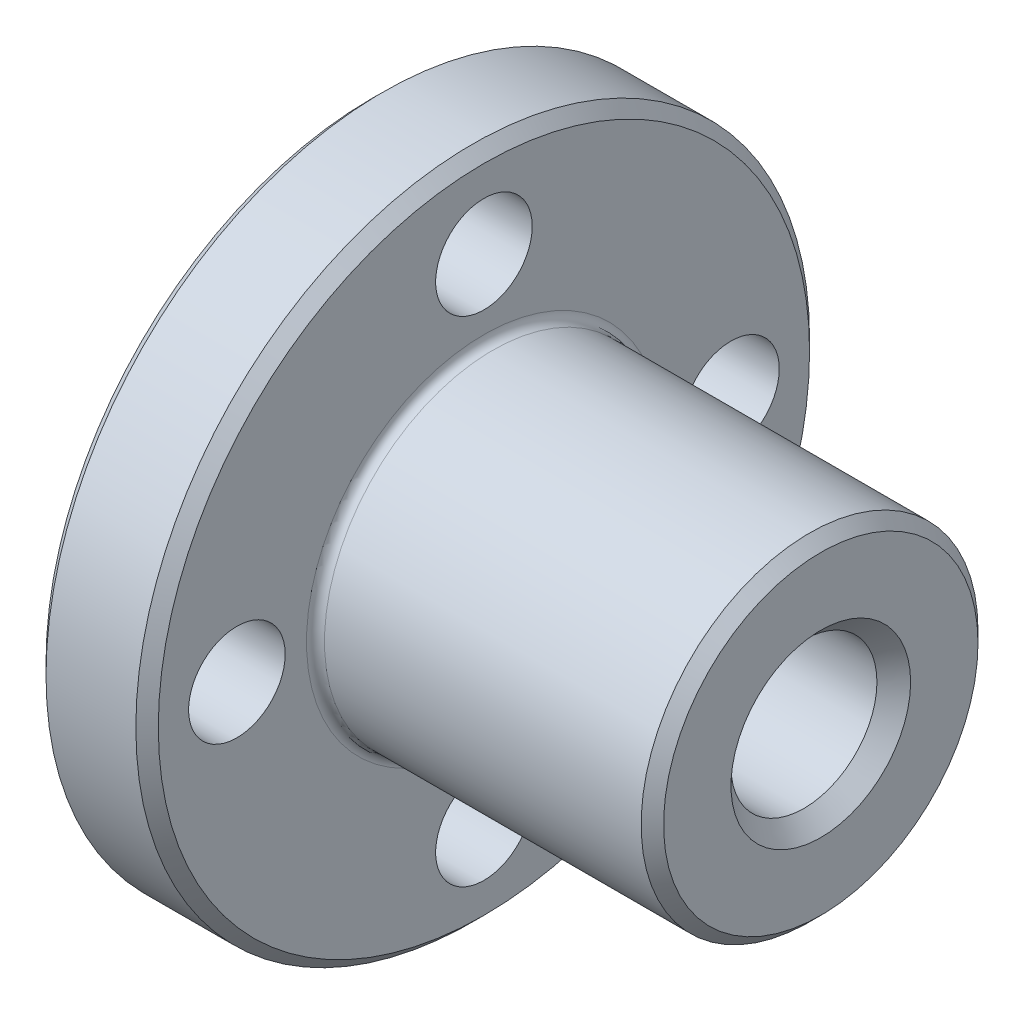
SolidWorks part; units mm, degrees
ref_plane "Front Plane" through (0, 0, 0) normal (0, 0, 1) x (1, 0, 0)
ref_plane "Top Plane" through (0, 0, 0) normal (0, 1, 0) x (1, 0, 0)
ref_plane "Right Plane" through (0, 0, 0) normal (1, 0, 0) x (0, 0, -1)
ref_plane "Plane1" through (0, 0, 0) normal (0, 0, -1) x (-1, 0, 0)
sketch "Sketch1" plane through (0, 0, 0) normal (0, 0, -1) x (-1, 0, 0)
  line L0 (-5, 15) -> (-5, 0)
  line L1 (-5, 0) -> (0, 0)
  line L2 (0, 0) -> (0, 15)
  line L3 (0, 15) -> (-5, 15)
  line L4 (-5, 0) -> (0, 0) construction
revolve "Revolve1" add sketch "Sketch1" angle 360 about L4
sketch "Sketch2" plane through (5, 0, 0) normal (1, 0, 0) x (0, 0, -1)
  circle A0 centre (0, 0) radius 7.5
extrude "Boss-Extrude1" add sketch "Sketch2" along normal blind 15
hole_wizard "Ø4.3 (4.3) Diameter Hole1" positions "Sketch4" profile "Sketch3" hole size "Ø4.3" standard "ANSI Metric"
sketch "Sketch4" plane through (5, 0, 0) normal (1, 0, 0) x (0, 0, -1)
  point P0 (-11, 0)
  point P1 (11, 0)
  point P2 (0, -11)
  point P3 (0, 11)
sketch "Sketch3" plane through (5, 0, 11) normal (0, 1, 0) x (0, 0, -1)
  line L0 (0, 0) -> (0, 5)
  line L1 (0, 5) -> (2.15, 5)
  line L2 (2.15, 5) -> (2.15, 0)
  line L5 (2.15, 0) -> (0, 0)
  line L11 (0, -6.35) -> (0, 107.95) construction
  dimension "Thru Hole Dia." = 4.3
  dimension "Thru Hole Depth" = 5
hole_wizard "Ø6.5 (6.5) Diameter Hole1" positions "Sketch6" profile "Sketch5" hole size "Ø6.5" standard "ANSI Metric"
sketch "Sketch6" plane through (0, 0, 0) normal (-1, 0, 0) x (0, 0, 1)
  point P0 (0, 0)
sketch "Sketch5" plane through (0, 0, 0) normal (0, 1, 0) x (0, 0, 1)
  line L0 (0, 0) -> (0, 20)
  line L1 (0, 20) -> (3.25, 20)
  line L2 (3.25, 20) -> (3.25, 0)
  line L5 (3.25, 0) -> (0, 0)
  line L11 (0, -6.35) -> (0, 107.95) construction
  dimension "Thru Hole Dia." = 6.5
  dimension "Thru Hole Depth" = 20
chamfer "Chamfer1" distance 0.75 angle 45 2 edges at (20, 0, 3.25) (0, 0, 3.25)
chamfer "Chamfer2" distance 0.5 angle 45 3 edges at (20, 0, -7.5) (0, 0, 15) (5, 0, 15)
fillet "Fillet1" radius 0.4 1 edges at (5, 0, -7.5)
